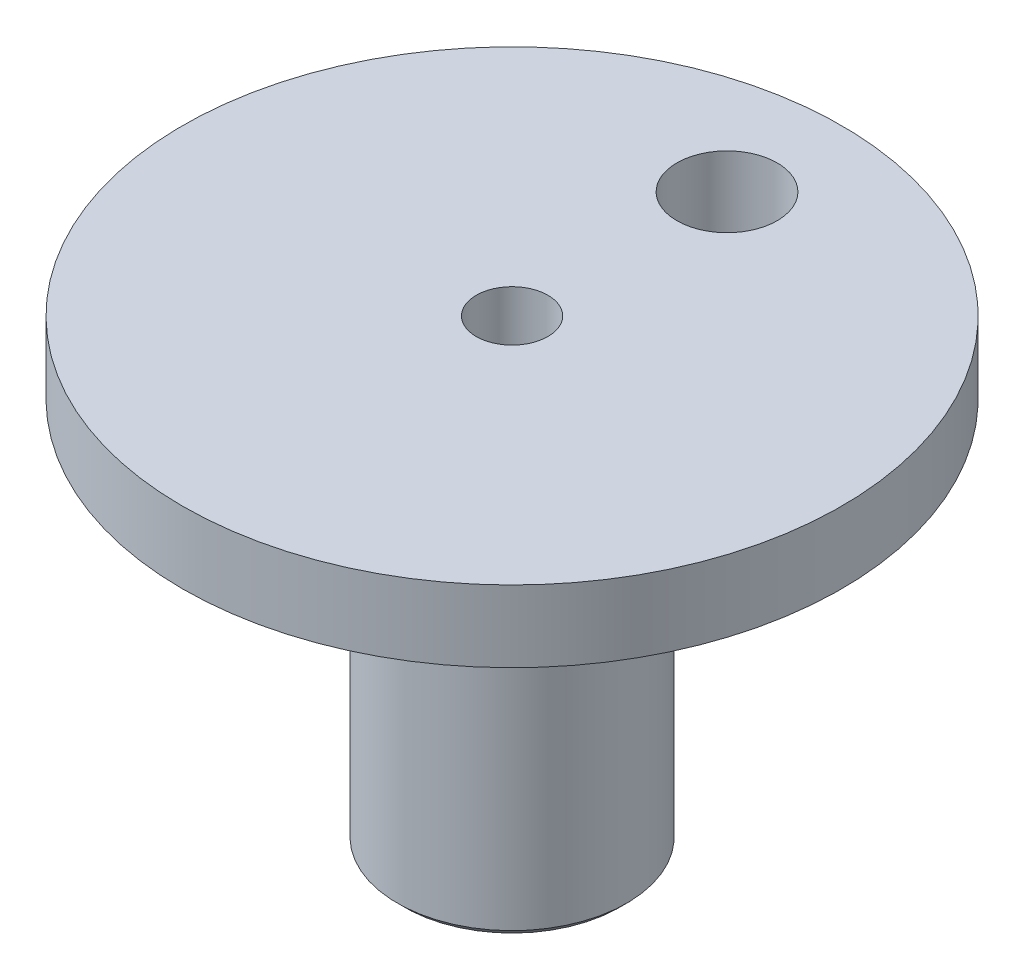
SolidWorks part; units mm, degrees
ref_plane "Front Plane" through (0, 0, 0) normal (0, 0, 1) x (1, 0, 0)
ref_plane "Top Plane" through (0, 0, 0) normal (0, 1, 0) x (1, 0, 0)
ref_plane "Right Plane" through (0, 0, 0) normal (1, 0, 0) x (0, 0, -1)
sketch "Sketch1" plane through (0, 0, 0) normal (0, 1, 0) x (1, 0, 0)
  circle A0 centre (0, 0) radius 23
  circle A1 centre (0, 15) radius 3.5
  dimension "D1" = 46
  dimension "D2" = 7
  dimension "D3" = 15
extrude "Boss-Extrude1" add sketch "Sketch1" along normal blind 5
sketch "Sketch2" plane through (0, 0, 0) normal (0, -1, 0) x (1, 0, 0)
  circle A0 centre (0, 0) radius 8
  dimension "D1" = 16
extrude "Boss-Extrude2" add sketch "Sketch2" along normal blind 27
sketch "Sketch3" plane through (0, 5, 0) normal (0, 1, 0) x (1, 0, 0)
  circle A0 centre (0, 0) radius 2.5
  dimension "D1" = 5
extrude "Cut-Extrude1" cut sketch "Sketch3" against normal through all
chamfer "Chamfer1" distance 0.5 angle 45 1 edges at (0, -27, -8)
